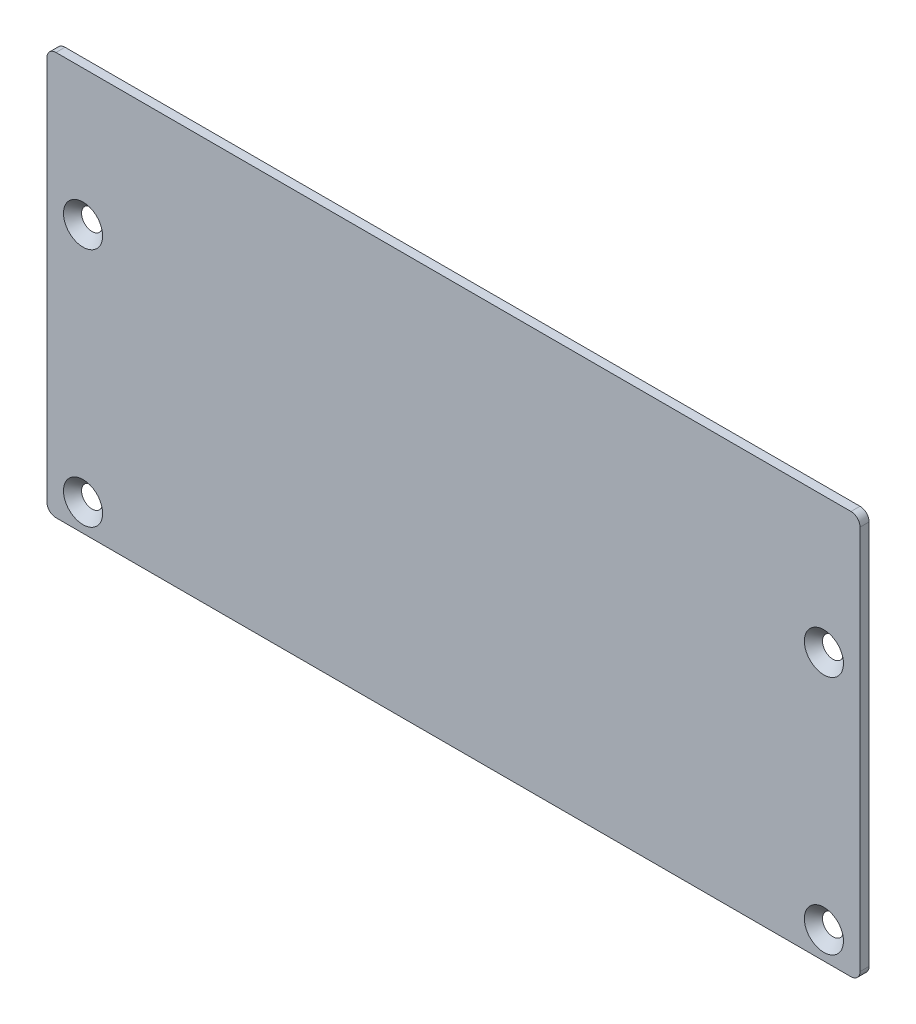
SolidWorks part; units mm, degrees
material "7075-T6, Plate (SS)"
ref_plane "Front Plane" through (0, 0, 0) normal (0, 0, 1) x (1, 0, 0)
ref_plane "Top Plane" through (0, 0, 0) normal (0, 1, 0) x (1, 0, 0)
ref_plane "Right Plane" through (0, 0, 0) normal (1, 0, 0) x (0, 0, -1)
sketch "Sketch2" plane through (0, 0, 0) normal (0, 0, 1) x (1, 0, 0)
  line L1 (-25.0658, 38.0217) -> (89.2342, 38.0217)
  line L2 (-25.0658, 38.0217) -> (-25.0658, -18.6203)
  line L3 (-25.0658, -18.6203) -> (89.2342, -18.6203)
  line L4 (89.2342, 38.0217) -> (89.2342, -18.6203)
  dimension "D1" = 56.642
  dimension "D2" = 114.3
extrude "Boss-Extrude1" add sketch "Sketch2" along normal blind 1.27
hole_wizard "CSK for M2.5 Countersunk Flat Head Screw1" positions "Sketch5" profile "Sketch6" countersink size "M2.5" standard "ISO" end condition up to next
sketch "Sketch5" plane through (0, 0, 1.27) normal (0, 0, 1) x (1, 0, 0)
  line L0 (-25.0658, 38.0217) -> (-25.0658, -18.6203) construction
  line L2 (-25.0658, -18.6203) -> (89.2342, -18.6203) construction
  line L3 (89.2342, 38.0217) -> (-25.0658, 38.0217) construction
  line L4 (89.2342, -18.6203) -> (89.2342, 38.0217) construction
  point P0 (-19.9858, 18.9717)
  point P2 (-19.9858, -14.8103)
  point P4 (84.1542, -14.8103)
  point P6 (84.1542, 18.9717)
  dimension "D1" = 5.08
  dimension "D2" = 5.08
  dimension "D3" = 3.81
  dimension "D4" = 19.05
  dimension "D5" = 19.05
  dimension "D6" = 5.08
  dimension "D7" = 3.81
  dimension "D8" = 5.08
sketch "Sketch6" plane through (-19.9858, 18.9717, 1.27) normal (1, 0, 0) x (0, -1, 0)
  line L0 (0, 0) -> (0, 1.27)
  line L1 (0, 1.27) -> (1.45, 1.27)
  line L2 (1.45, 1.27) -> (1.45, 1.3)
  line L3 (1.45, 1.3) -> (2.75, 0)
  line L5 (2.75, 0) -> (0, 0)
  line L6 (-1.45, 1.3) -> (-2.75, 0) construction
  line L11 (0, -6.35) -> (0, 107.95) construction
  dimension "Thru Hole Dia." = 2.9
  dimension "Thru Hole Depth" = 1.27
  dimension "Near C'Sink Dia." = 5.5
  dimension "Near C'Sink Angle" = 90
fillet "Fillet1" radius 1.27 4 edges at (-25.0658, -18.6203, 0.635) (89.2342, -18.6203, 0.635) (89.2342, 38.0217, 0.635) (-25.0658, 38.0217, 0.635)
